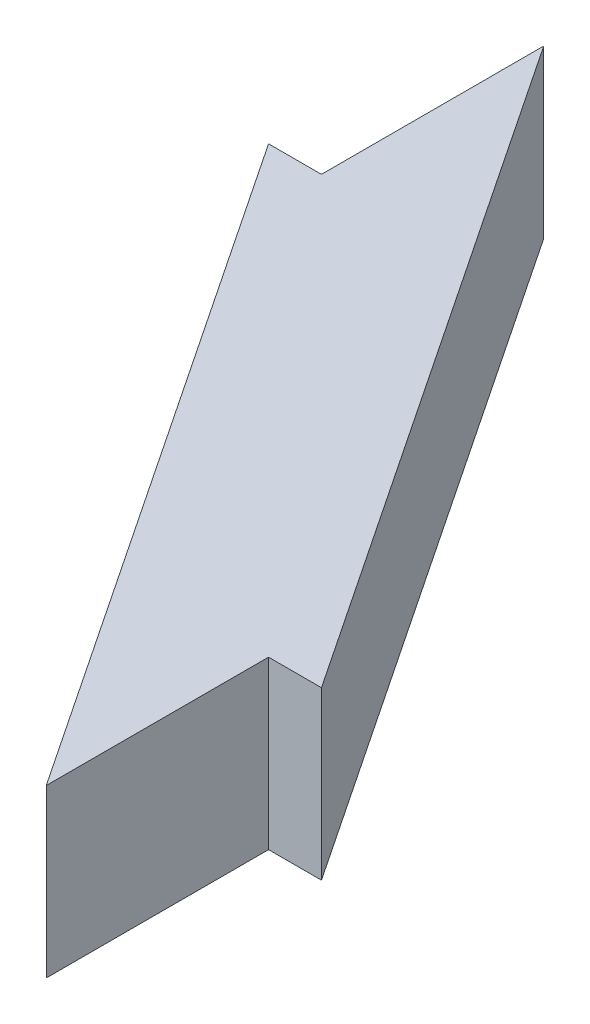
SolidWorks part; units mm, degrees
ref_plane "Front Plane" through (0, 0, 0) normal (0, 0, 1) x (1, 0, 0)
ref_plane "Top Plane" through (0, 0, 0) normal (0, 1, 0) x (1, 0, 0)
ref_plane "Right Plane" through (0, 0, 0) normal (1, 0, 0) x (0, 0, -1)
sketch "Sketch1" plane through (0, 0, 0) normal (0, 1, 0) x (1, 0, 0)
  line L0 (22.3774, -50.8) -> (-28.4226, 25.4)
  line L1 (-22.3774, 50.8) -> (28.4226, -25.4)
  line L2 (-22.3774, 50.8) -> (-22.3774, 25.4)
  line L3 (-22.3774, 25.4) -> (-28.4226, 25.4)
  line L4 (28.4226, -25.4) -> (22.3774, -25.4)
  line L5 (22.3774, -25.4) -> (22.3774, -50.8)
  line L6 (22.3774, -25.4) -> (-22.3774, 25.4) construction
  line L8 (22.3774, -63.5) -> (28.4226, -63.5) construction
  line L9 (22.3774, -63.5) -> (22.3774, -25.4) construction
  line L10 (22.3774, -25.4) -> (28.4226, -25.4) construction
  line L11 (28.4226, -63.5) -> (28.4226, -25.4) construction
  line L12 (22.3774, -63.5) -> (28.4226, -25.4) construction
  line L13 (22.3774, -25.4) -> (28.4226, -63.5) construction
  line L14 (-28.4226, 63.5) -> (-22.3774, 63.5) construction
  line L15 (-28.4226, 63.5) -> (-28.4226, 25.4) construction
  line L16 (-28.4226, 25.4) -> (-22.3774, 25.4) construction
  line L17 (-22.3774, 63.5) -> (-22.3774, 25.4) construction
  line L18 (-28.4226, 63.5) -> (-22.3774, 25.4) construction
  line L19 (-28.4226, 25.4) -> (-22.3774, 63.5) construction
  point P4 (25.4, -44.45)
  point P12 (0, 0)
  point P13 (-37.2059, 44.45)
  point P15 (-25.4, 44.45)
  dimension "D1" = 25.4
  dimension "D2" = 6.0452
  dimension "D3" = 50.8
  dimension "D4" = 6.0452
  dimension "D5" = 38.1
  dimension "D6" = 50.8
extrude "Boss-Extrude1" add sketch "Sketch1" along normal mid plane 19.05
